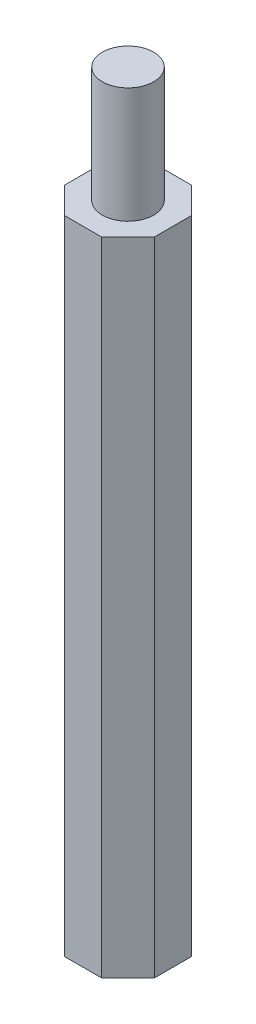
SolidWorks part; units mm, degrees
ref_plane "Plan de face" through (0, 0, 0) normal (0, 0, 1) x (1, 0, 0)
ref_plane "Plan de dessus" through (0, 0, 0) normal (0, 1, 0) x (1, 0, 0)
ref_plane "Plan de droite" through (0, 0, 0) normal (1, 0, 0) x (0, 0, -1)
sketch "Esquisse1" plane through (0, 0, 0) normal (0, 1, 0) x (1, 0, 0)
  line L0 (-1.4497, 3.5) -> (1.4497, 3.5)
  line L1 (1.4497, 3.5) -> (3.5, 1.4497)
  line L2 (3.5, 1.4497) -> (3.5, -1.4497)
  line L3 (3.5, -1.4497) -> (1.4497, -3.5)
  line L4 (1.4497, -3.5) -> (-1.4497, -3.5)
  line L5 (-1.4497, -3.5) -> (-3.5, -1.4497)
  line L6 (-3.5, -1.4497) -> (-3.5, 1.4497)
  line L7 (-3.5, 1.4497) -> (-1.4497, 3.5)
  line L8 (0, 3.5) -> (0, -3.5) construction
  dimension "D1" = 7
extrude "Extrusion1" add sketch "Esquisse1" along normal mid plane 50
sketch "Esquisse2" plane through (0, 25, 0) normal (0, 1, 0) x (1, 0, 0)
  circle A0 centre (0, 0) radius 2
  dimension "D1" = 4
extrude "Extrusion2" add sketch "Esquisse2" along normal blind 9
sketch "Esquisse3" plane through (0, -25, 0) normal (0, -1, 0) x (1, 0, 0)
  circle A0 centre (0, 0) radius 2
  dimension "D1" = 4
extrude "Enlèv. mat.-Extru.1" cut sketch "Esquisse3" against normal blind 9
